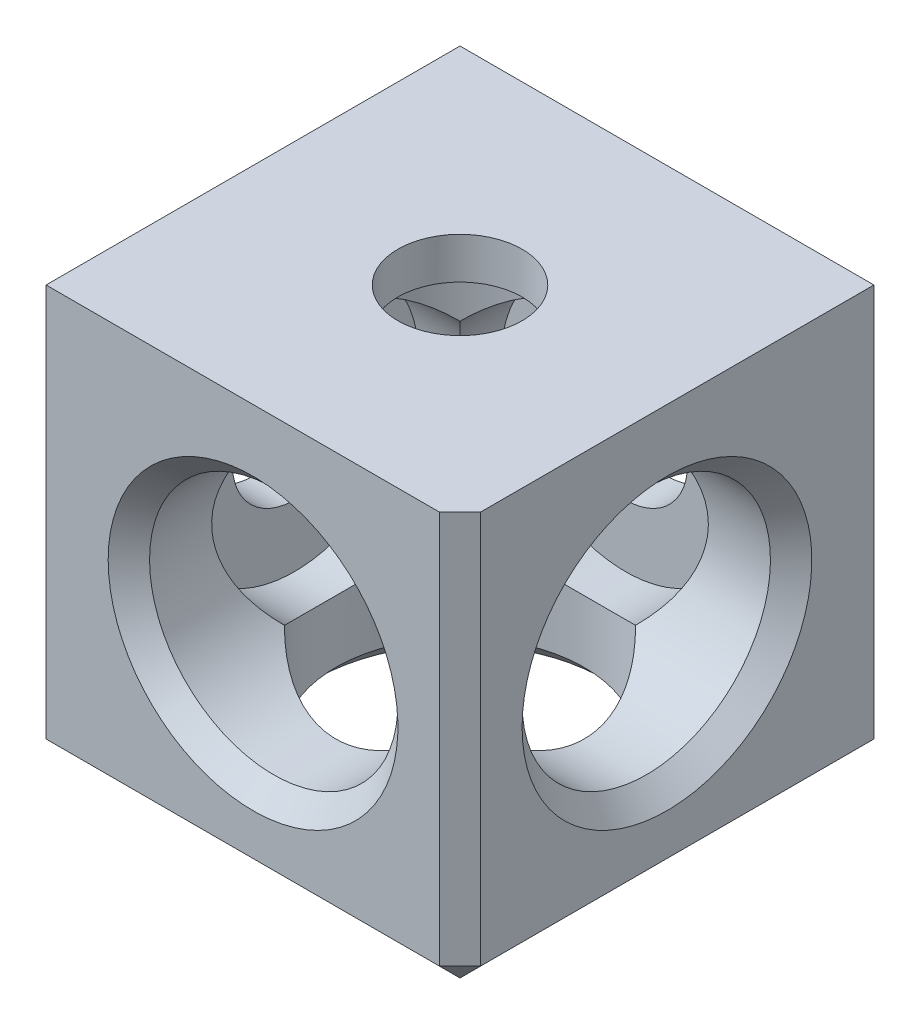
SolidWorks part; units mm, degrees
ref_plane "前视基准面" through (0, 0, 0) normal (0, 0, 1) x (1, 0, 0)
ref_plane "上视基准面" through (0, 0, 0) normal (0, 1, 0) x (1, 0, 0)
ref_plane "右视基准面" through (0, 0, 0) normal (1, 0, 0) x (0, 0, -1)
sketch "草图1" plane through (0, 0, 0) normal (0, 0, 1) x (1, 0, 0)
  line L1 (-10, -10) -> (10, -10)
  line L2 (-10, -10) -> (-10, 10)
  line L3 (-10, 10) -> (10, 10)
  line L4 (10, -10) -> (10, 10)
  line L5 (-10, -10) -> (10, 10) construction
  line L6 (-10, 10) -> (10, -10) construction
  point P0 (0, 0)
  dimension "D1" = 20
extrude "凸台-拉伸1" add sketch "草图1" along normal blind 20
sketch "草图2" plane through (0, 0, 0) normal (0, 0, -1) x (-1, 0, 0)
  circle A0 centre (0, 0) radius 3
  dimension "D1" = 6
extrude "切除-拉伸1" cut sketch "草图2" against normal up to surface (20 mm away) contours A0 up to face at (0, 0, 20)
sketch "草图3" plane through (10, 0, 0) normal (1, 0, 0) x (0, 0, -1)
  line L1 (-20, 10) -> (0, 10) construction
  line L3 (-20, 10) -> (0, -10) construction
  line L4 (-20, -10) -> (-20, 10) construction
  circle A0 centre (-10, 0) radius 3
  point P4 (0, 0)
  dimension "D1" = 6
extrude "切除-拉伸2" cut sketch "草图3" against normal up to surface (20 mm away) contours A0 up to face at (-10, 0, 10)
sketch "草图4" plane through (0, 10, 0) normal (0, 1, 0) x (1, 0, 0)
  line L0 (-10, 0) -> (10, -20) construction
  circle A0 centre (0, -10) radius 3
  point P6 (0, 0)
  dimension "D1" = 6
extrude "切除-拉伸3" cut sketch "草图4" against normal up to surface (20 mm away) up to face at (0, -10, 10)
sketch "草图5" plane through (10, 0, 0) normal (1, 0, 0) x (0, 0, -1)
  circle A0 centre (-10, 0) radius 6
  circle A1 centre (-10, 0) radius 3 construction
  dimension "D1" = 12
extrude "切除-拉伸4" cut sketch "草图5" against normal blind 18
sketch "草图6" plane through (0, 0, 20) normal (0, 0, 1) x (1, 0, 0)
  circle A0 centre (0, 0) radius 6
  dimension "D1" = 12
extrude "切除-拉伸5" cut sketch "草图6" against normal blind 18
sketch "草图7" plane through (0, -10, 0) normal (0, -1, 0) x (1, 0, 0)
  circle A0 centre (0, 10) radius 6
  dimension "D1" = 12
extrude "切除-拉伸6" cut sketch "草图7" against normal blind 18
chamfer "倒角1" distance 1 angle 45 3 edges at (0, -10, 20) (10, -10, 10) (10, 0, 20)
chamfer "倒角2" distance 1 angle 45 3 edges at (0, -10, 4) (10, 0, 4) (6, 0, 20)
